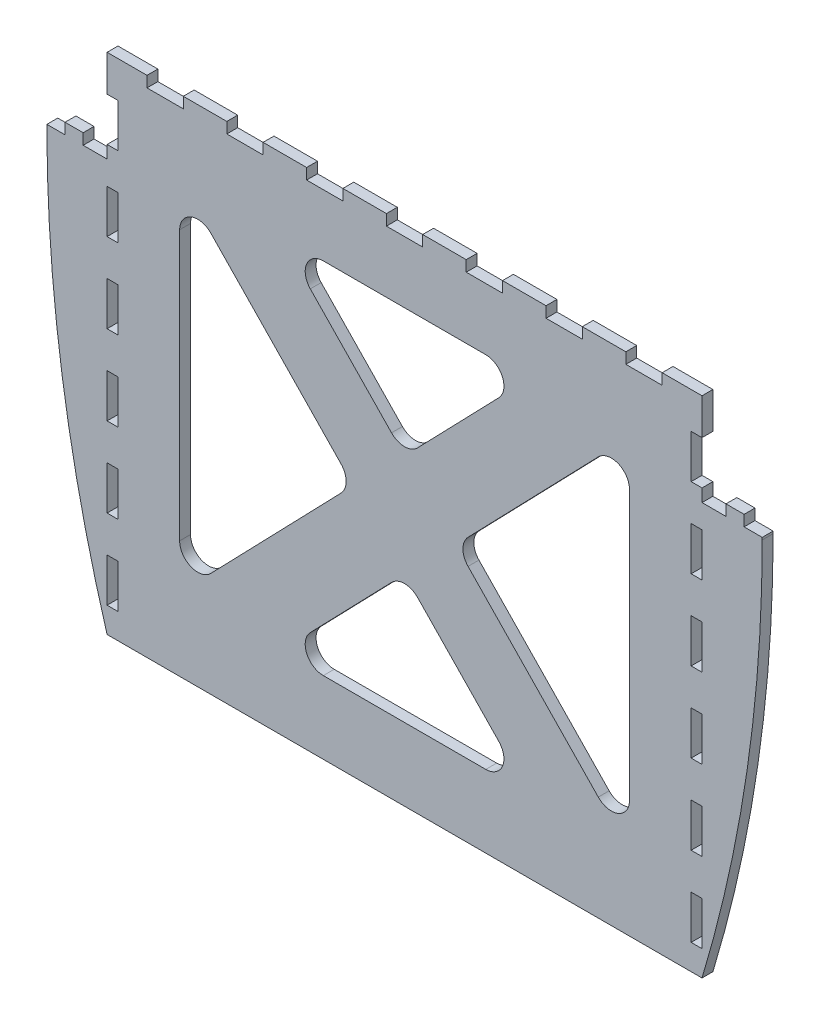
SolidWorks part; units mm, degrees
material "birch 3mm plywood"
ref_plane "Front Plane" through (0, 0, 0) normal (0, 0, 1) x (1, 0, 0)
ref_plane "Top Plane" through (0, 0, 0) normal (0, 1, 0) x (1, 0, 0)
ref_plane "Right Plane" through (0, 0, 0) normal (1, 0, 0) x (0, 0, -1)
sketch "Sketch1" plane through (0, 0, 152) normal (0, 0, 1) x (1, 0, 0)
  line L1 (-82, 69.5) -> (82, 69.5)
  line L2 (-82, 69.5) -> (-82, 44)
  line L3 (-82, -69.5) -> (82, -69.5)
  line L4 (82, 69.5) -> (82, 44)
  line L6 (-62, -37.1347) -> (-62, 37.1347)
  line L7 (-53.4053, 40.61) -> (-17.504, 3.4753)
  line L8 (-88.6, 47) -> (-93.6, 47)
  line L9 (-98.6, 44) -> (-98.6, 43.3771)
  line L10 (0, 69.5) -> (0, -69.5) construction
  line L12 (75, -62.5) -> (-75, -62.5) construction
  line L13 (75, 62.5) -> (75, -62.5) construction
  line L14 (-75, -62.5) -> (-75, 62.5) construction
  line L15 (-75, 62.5) -> (75, 62.5) construction
  line L18 (22.3929, 49.5) -> (-22.3929, 49.5)
  line L19 (-17.504, -3.4753) -> (-53.4053, -40.61)
  line L20 (-25.9877, 41.0247) -> (-3.5947, 17.8624)
  line L21 (3.5947, 17.8624) -> (25.9877, 41.0247)
  line L23 (53.4053, 40.61) -> (17.504, 3.4753)
  line L24 (62, -37.1347) -> (62, 37.1347)
  line L25 (17.504, -3.4753) -> (53.4053, -40.61)
  line L26 (-75, 0) -> (75, 0) construction
  line L27 (-25.9877, -41.0247) -> (-3.5947, -17.8624)
  line L28 (22.3929, -49.5) -> (-22.3929, -49.5)
  line L29 (3.5947, -17.8624) -> (25.9877, -41.0247)
  line L30 (0, 14.1442) -> (0, -14.1442) construction
  line L31 (-14.1442, 0) -> (14.1442, 0) construction
  line L32 (0, 14.1442) -> (0, -14.1442) construction
  line L33 (-93.6, 47) -> (-93.6, 44)
  line L34 (-93.6, 44) -> (-98.6, 44)
  line L35 (-88.6, 47) -> (-88.6, 44)
  line L36 (-88.6, 44) -> (-82, 44)
  line L37 (98.6, 44) -> (98.6, 43.3771)
  line L38 (93.6, 44) -> (98.6, 44)
  line L39 (93.6, 47) -> (93.6, 44)
  line L40 (88.6, 47) -> (93.6, 47)
  line L41 (88.6, 47) -> (88.6, 44)
  line L42 (88.6, 44) -> (82, 44)
  arc A0 (-53.4053, -40.61) -> (-62, -37.1347) centre (-57, -37.1347) cw
  arc A1 (-17.504, -3.4753) -> (-17.504, 3.4753) centre (-21.0988, 0) ccw
  arc A2 (-53.4053, 40.61) -> (-62, 37.1347) centre (-57, 37.1347) ccw
  arc A3 (25.9877, -41.0247) -> (22.3929, -49.5) centre (22.3929, -44.5) cw
  arc A4 (-25.9877, -41.0247) -> (-22.3929, -49.5) centre (-22.3929, -44.5) ccw
  arc A5 (-3.5947, -17.8624) -> (3.5947, -17.8624) centre (0, -21.3377) cw
  arc A6 (17.504, 3.4753) -> (17.504, -3.4753) centre (21.0988, 0) ccw
  arc A7 (53.4053, -40.61) -> (62, -37.1347) centre (57, -37.1347) ccw
  arc A8 (62, 37.1347) -> (53.4053, 40.61) centre (57, 37.1347) ccw
  arc A9 (-25.9877, 41.0247) -> (-22.3929, 49.5) centre (-22.3929, 44.5) cw
  arc A10 (25.9877, 41.0247) -> (22.3929, 49.5) centre (22.3929, 44.5) ccw
  arc A11 (3.5947, 17.8624) -> (-3.5947, 17.8624) centre (0, 21.3377) cw
  arc A12 (-98.6, 43.3771) -> (-82, -69.5) centre (293.4723, 43.3771) ccw
  arc A14 (98.6, 43.3771) -> (82, -69.5) centre (-293.4723, 43.3771) cw
  point P14 (0, 0)
  point P15 (0, 0)
  point P32 (-62, 49.5)
  point P35 (34.1815, -49.5)
  point P38 (-34.1815, -49.5)
  point P51 (-34.1815, 49.5)
  point P54 (34.1815, 49.5)
  dimension "D9" = 5
  dimension "D10" = 5
  dimension "D2" = 20
  dimension "D3" = 7
  dimension "D4" = 7
  dimension "D5" = 20
  dimension "D6" = 20
  dimension "D7" = 20
  dimension "D8" = 20
  dimension "D11" = 150
  dimension "D12" = 125
  dimension "D13" = 7
  dimension "D14" = 22.5
  dimension "D15" = 16.6
  dimension "D16" = 3
  dimension "D17" = 5
  dimension "D18" = 5
extrude "Boss-Extrude1" add sketch "Sketch1" along normal blind 3
sketch "Sketch2" plane through (0, 0, 155) normal (0, 0, 1) x (1, 0, 0)
  line L0 (0, 69.5) -> (0, -69.5) construction
  line L1 (17, 69.5) -> (17, 66.5)
  line L2 (-5, 69.5) -> (5, 69.5)
  line L3 (-5, 69.5) -> (-5, 66.5)
  line L4 (-82, 69.5) -> (-82, 44)
  line L5 (-82, -69.5) -> (82, -69.5)
  line L6 (82, 44) -> (82, 69.5)
  line L7 (82, 69.5) -> (-82, 69.5)
  line L8 (-82, 69.5) -> (-82, 44)
  line L9 (-82, -69.5) -> (82, -69.5)
  line L10 (82, 44) -> (82, 69.5)
  line L11 (82, 69.5) -> (-82, 69.5)
  line L12 (-5, 66.5) -> (5, 66.5)
  line L13 (5, 69.5) -> (5, 66.5)
  line L14 (17, 69.5) -> (27, 69.5)
  line L15 (27, 69.5) -> (27, 66.5)
  line L16 (17, 66.5) -> (27, 66.5)
  line L17 (39, 69.5) -> (39, 66.5)
  line L18 (39, 69.5) -> (49, 69.5)
  line L19 (49, 69.5) -> (49, 66.5)
  line L20 (39, 66.5) -> (49, 66.5)
  line L21 (61, 69.5) -> (61, 66.5)
  line L22 (61, 69.5) -> (71, 69.5)
  line L23 (71, 69.5) -> (71, 66.5)
  line L24 (61, 66.5) -> (71, 66.5)
  line L25 (-27, 69.5) -> (-27, 66.5)
  line L26 (-27, 69.5) -> (-17, 69.5)
  line L27 (-17, 69.5) -> (-17, 66.5)
  line L28 (-27, 66.5) -> (-17, 66.5)
  line L29 (-49, 69.5) -> (-49, 66.5)
  line L30 (-49, 69.5) -> (-39, 69.5)
  line L31 (-39, 69.5) -> (-39, 66.5)
  line L32 (-49, 66.5) -> (-39, 66.5)
  line L33 (-71, 69.5) -> (-71, 66.5)
  line L34 (-71, 69.5) -> (-61, 69.5)
  line L35 (-61, 69.5) -> (-61, 66.5)
  line L36 (-71, 66.5) -> (-61, 66.5)
  line L37 (-82, 37.5) -> (-82, 25.5)
  line L38 (-82, 59.5) -> (-79, 59.5)
  line L39 (-82, 59.5) -> (-82, 47.5)
  line L40 (-82, 47.5) -> (-79, 47.5)
  line L41 (-79, 59.5) -> (-79, 47.5)
  line L42 (-82, 37.5) -> (-79, 37.5)
  line L43 (-79, 37.5) -> (-79, 25.5)
  line L44 (-82, 25.5) -> (-79, 25.5)
  line L45 (-82, 15.5) -> (-82, 3.5)
  line L46 (-82, 15.5) -> (-79, 15.5)
  line L47 (-79, 15.5) -> (-79, 3.5)
  line L48 (-82, 3.5) -> (-79, 3.5)
  line L49 (-82, -6.5) -> (-82, -18.5)
  line L50 (-82, -6.5) -> (-79, -6.5)
  line L51 (-79, -6.5) -> (-79, -18.5)
  line L52 (-82, -18.5) -> (-79, -18.5)
  line L53 (-82, -28.5) -> (-82, -40.5)
  line L54 (-82, -28.5) -> (-79, -28.5)
  line L55 (-79, -28.5) -> (-79, -40.5)
  line L56 (-82, -40.5) -> (-79, -40.5)
  line L57 (-82, -50.5) -> (-82, -62.5)
  line L58 (-82, -50.5) -> (-79, -50.5)
  line L59 (-79, -50.5) -> (-79, -62.5)
  line L60 (-82, -62.5) -> (-79, -62.5)
  line L65 (82, -50.5) -> (79, -50.5)
  line L66 (79, -50.5) -> (79, -62.5)
  line L67 (82, -62.5) -> (79, -62.5)
  line L68 (82, -50.5) -> (82, -62.5)
  line L69 (82, -28.5) -> (79, -28.5)
  line L70 (79, -28.5) -> (79, -40.5)
  line L71 (82, -40.5) -> (79, -40.5)
  line L72 (82, -28.5) -> (82, -40.5)
  line L73 (82, -6.5) -> (79, -6.5)
  line L74 (79, -6.5) -> (79, -18.5)
  line L75 (82, -18.5) -> (79, -18.5)
  line L76 (82, -6.5) -> (82, -18.5)
  line L77 (82, 15.5) -> (79, 15.5)
  line L78 (79, 15.5) -> (79, 3.5)
  line L79 (82, 3.5) -> (79, 3.5)
  line L80 (82, 15.5) -> (82, 3.5)
  line L81 (82, 37.5) -> (79, 37.5)
  line L82 (79, 37.5) -> (79, 25.5)
  line L83 (82, 25.5) -> (79, 25.5)
  line L84 (82, 37.5) -> (82, 25.5)
  line L85 (82, 47.5) -> (79, 47.5)
  line L86 (79, 59.5) -> (79, 47.5)
  line L87 (82, 59.5) -> (79, 59.5)
  line L88 (82, 59.5) -> (82, 47.5)
  line L97 (-88.6, 47) -> (-93.6, 47)
  line L98 (-88.6, 47) -> (-93.6, 47)
  line L99 (-98.6, 44) -> (-98.6, 43.3771)
  line L100 (-98.6, 44) -> (-98.6, 43.3771)
  line L101 (98.6, 43.3771) -> (98.6, 44)
  line L103 (98.6, 43.3771) -> (98.6, 44)
  line L109 (-82, 44) -> (-88.6, 44)
  line L110 (-82, 44) -> (-88.6, 44)
  line L111 (-88.6, 44) -> (-88.6, 47)
  line L112 (-88.6, 44) -> (-88.6, 47)
  line L113 (-93.6, 47) -> (-93.6, 44)
  line L114 (-93.6, 47) -> (-93.6, 44)
  line L115 (-93.6, 44) -> (-98.6, 44)
  line L116 (-93.6, 44) -> (-98.6, 44)
  line L121 (98.6, 44) -> (93.6, 44)
  line L122 (98.6, 44) -> (93.6, 44)
  line L123 (93.6, 44) -> (93.6, 47)
  line L124 (93.6, 44) -> (93.6, 47)
  line L125 (93.6, 47) -> (88.6, 47)
  line L126 (93.6, 47) -> (88.6, 47)
  line L127 (88.6, 47) -> (88.6, 44)
  line L128 (88.6, 47) -> (88.6, 44)
  line L129 (88.6, 44) -> (82, 44)
  line L130 (88.6, 44) -> (82, 44)
  arc A2 (-98.6, 43.3771) -> (-82, -69.5) centre (293.4723, 43.3771) ccw
  arc A3 (-98.6, 43.3771) -> (-82, -69.5) centre (293.4723, 43.3771) ccw
  arc A4 (82, -69.5) -> (98.6, 43.3771) centre (-293.4723, 43.3771) ccw
  arc A6 (82, -69.5) -> (98.6, 43.3771) centre (-293.4723, 43.3771) ccw
  point P10 (0, 66.5)
  line M64 (82, 44) -> (82, 69.5)
  line M65 (82, 69.5) -> (-82, 69.5)
  dimension "D2" = 10
  dimension "D3" = 3
  dimension "D6" = 12
  dimension "D7" = 12
  dimension "D8" = 3
  dimension "D9" = 12
  dimension "D10" = 10
  dimension "D12" = 10
  dimension "D1" = 0
  dimension "D4" = 4
  dimension "D5" = 4
  dimension "D11" = 6
extrude "Cut-Extrude1" cut sketch "Sketch2" against normal blind 10 contours L8 L44 L43 L42 | L33 L36 L35 L11 | L29 L32 L31 M65 | L25 L28 L27 L11 | L0 L12 L13 M65 | L0 L11 L3 L12 | L1 L16 L15 L11 | L17 L20 L19 L11 | L21 L24 L23 L11 | L87 L86 L85 M64 | L79 L77 L78 M64 | L75 L10 L73 L74 | L71 L69 L70 M64 | L67 L10 L65 L66 | L41 L40 L39 L38 | L47 L48 L45 L46 | L51 L52 L49 L50 | L55 L56 L53 L54 | L59 L60 L57 L58 | L82 L83 L84 L81
